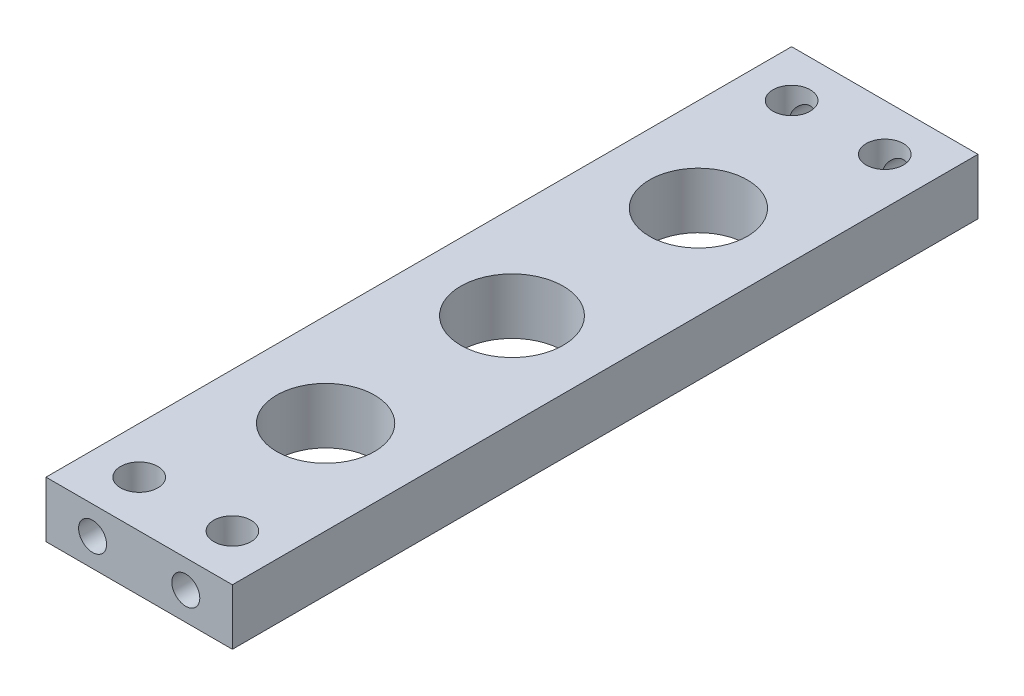
SolidWorks part; units mm, degrees
material "Beech"
ref_plane "Front Plane" through (0, 0, 0) normal (0, 0, 1) x (1, 0, 0)
ref_plane "Top Plane" through (0, 0, 0) normal (0, 1, 0) x (1, 0, 0)
ref_plane "Right Plane" through (0, 0, 0) normal (1, 0, 0) x (0, 0, -1)
sketch "Sketch1" plane through (0, 0, 0) normal (0, 1, 0) x (1, 0, 0)
  line L1 (20, -80) -> (-20, -80)
  line L2 (20, -80) -> (20, 80)
  line L3 (20, 80) -> (-20, 80)
  line L4 (-20, -80) -> (-20, 80)
  line L5 (20, -80) -> (-20, 80) construction
  line L6 (20, 80) -> (-20, -80) construction
  circle A0 centre (0, 0) radius 11
  circle A1 centre (0, 40) radius 10.5
  circle A2 centre (0, -40) radius 10.5
  dimension "D1" = 22
  dimension "D2" = 21
  dimension "D3" = 21
  dimension "D4" = 40
  dimension "D5" = 40
  dimension "D6" = 40
  dimension "D7" = 160
extrude "Boss-Extrude1" add sketch "Sketch1" along normal blind 12
sketch "Sketch4" plane through (0, 12, 0) normal (0, 1, 0) x (1, 0, 0)
  line L0 (-40.443, 70) -> (34.6927, 70) construction
  line L1 (-20, 80) -> (-20, -80) construction
  line L2 (20, -80) -> (20, 80) construction
  line L3 (20, 80) -> (-20, 80) construction
  circle A0 centre (-10, 70) radius 4
  circle A1 centre (10, 70) radius 4
  dimension "D1" = 8
  dimension "D2" = 8
  dimension "D3" = 10
  dimension "D4" = 10
  dimension "D5" = 10
extrude "Cut-Extrude3" cut sketch "Sketch4" against normal up to next
sketch "Sketch5" plane through (0, 0, -80) normal (0, 0, -1) x (-1, 0, 0)
  line L0 (33.3705, 6) -> (-34.1913, 6) construction
  line L1 (20, 12) -> (20, 0) construction
  line L2 (-20, 12) -> (-20, 0) construction
  circle A0 centre (10, 6) radius 3
  circle A1 centre (-10, 6) radius 3
  dimension "D1" = 6
  dimension "D2" = 10
  dimension "D3" = 6
  dimension "D4" = 10
extrude "Cut-Extrude4" cut sketch "Sketch5" against normal up to next
mirror "Mirror1" about plane through (0, 0, 0) normal (0, 0, 1) of "Cut-Extrude3", "Cut-Extrude4"
